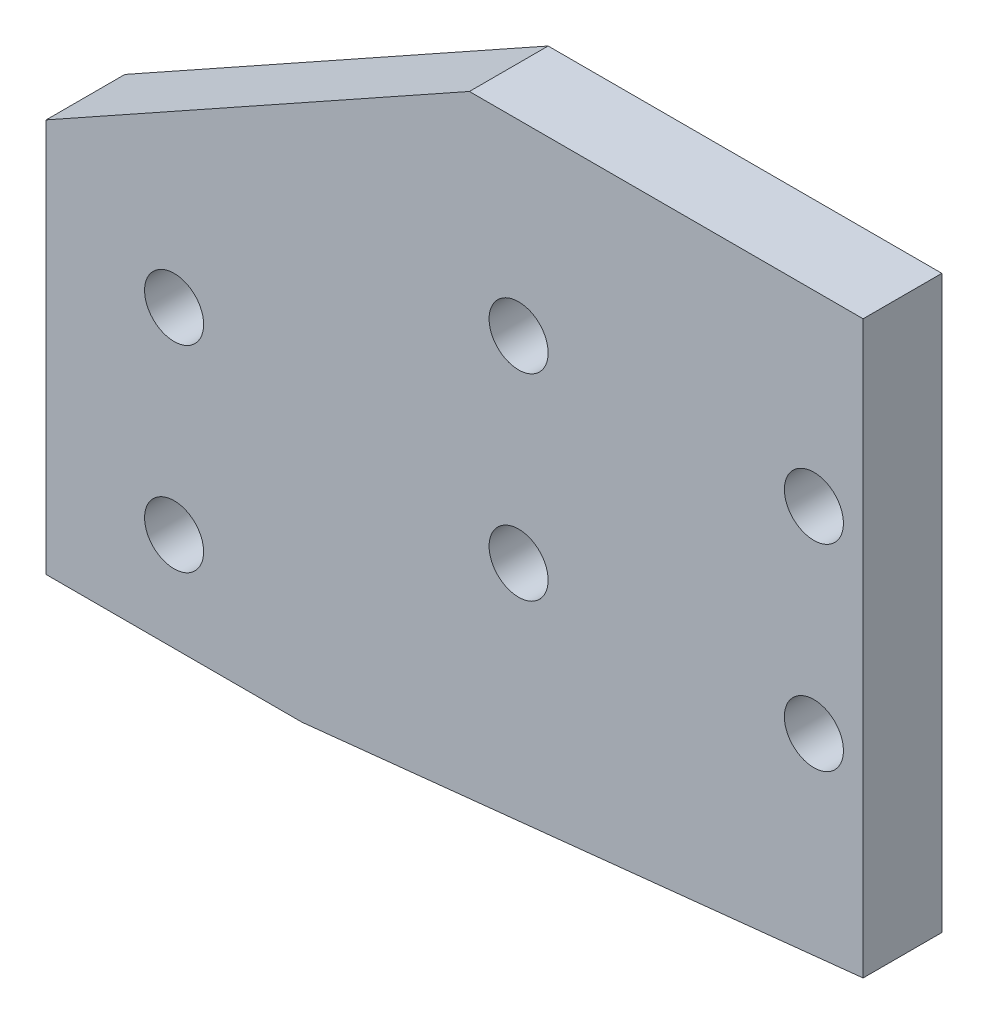
SolidWorks part; units mm, degrees
ref_plane "前视基准面" through (0, 0, 0) normal (0, 0, 1) x (1, 0, 0)
ref_plane "上视基准面" through (0, 0, 0) normal (0, 1, 0) x (1, 0, 0)
ref_plane "右视基准面" through (0, 0, 0) normal (1, 0, 0) x (0, 0, -1)
other "Configuration Table"
sketch "草图1" plane through (0, 0, 0) normal (0, 0, 1) x (1, 0, 0)
  line L0 (0, 0) -> (13, 0)
  line L1 (13, 0) -> (41.5, 3)
  line L2 (41.5, 3) -> (41.5, 32)
  line L3 (41.5, 32) -> (21.5, 32)
  line L4 (21.5, 32) -> (0, 20)
  line L5 (0, 20) -> (0, 0)
  line L6 (0, 20) -> (13, 20) construction
  line L7 (13, 20) -> (13, 0) construction
  line L8 (21.5, 32) -> (21.5, 3) construction
  line L9 (21.5, 3) -> (41.5, 3) construction
  line L10 (0, 10) -> (13, 10) construction
  line L11 (6.5, 10) -> (6.5, 15) construction
  line L12 (21.5, 17.5) -> (41.5, 17.5) construction
  line L13 (31.5, 17.5) -> (31.5, 32) construction
  circle A0 centre (6.5, 15) radius 1.5
  circle A1 centre (6.5, 5) radius 1.5
  circle A2 centre (24, 12.5) radius 1.5
  circle A3 centre (39, 12.5) radius 1.5
  circle A4 centre (24, 22.5) radius 1.5
  circle A5 centre (39, 22.5) radius 1.5
  dimension "D1" = 3
  dimension "D2" = 3
  dimension "D5" = 10
  dimension "D6" = 15
  dimension "D9" = 10
  dimension "D3" = 20
  dimension "D4" = 29
  dimension "D7" = 20
  dimension "D8" = 13
  dimension "D10" = 25
  dimension "D11" = 7.5
extrude "凸台-拉伸1" add sketch "草图1" along normal blind 4
